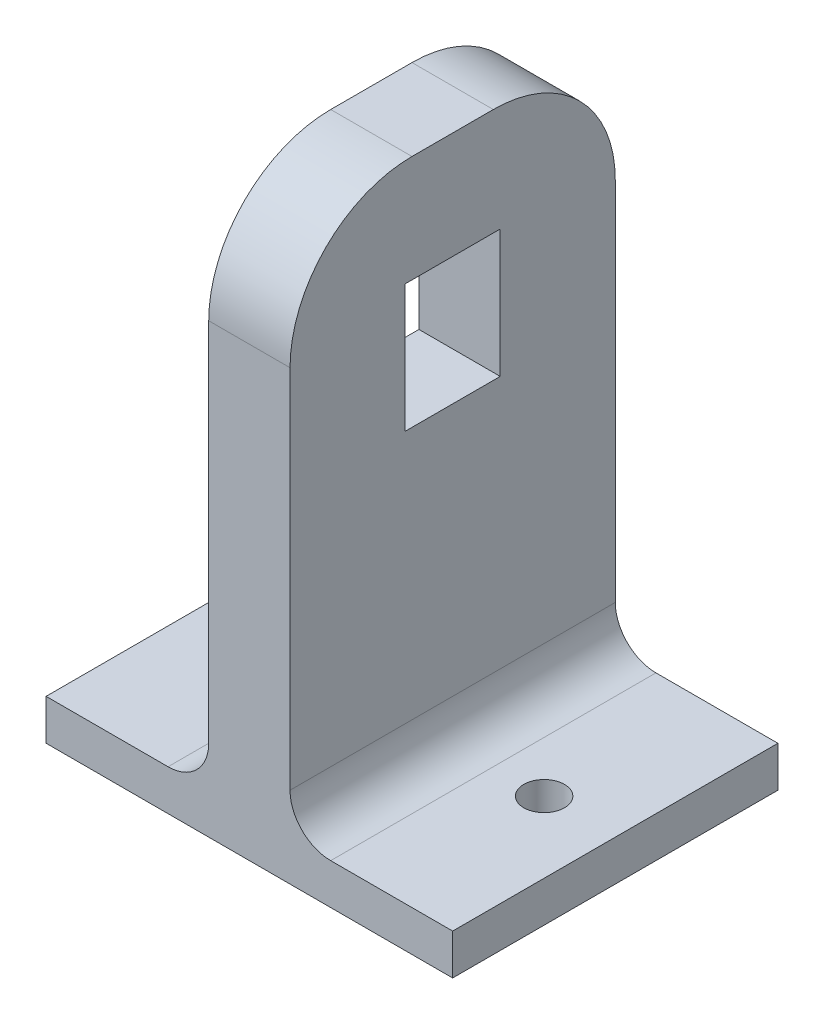
SolidWorks part; units mm, degrees
material "ABS"
ref_plane "Front Plane" through (0, 0, 0) normal (0, 0, 1) x (1, 0, 0)
ref_plane "Top Plane" through (0, 0, 0) normal (0, 1, 0) x (1, 0, 0)
ref_plane "Right Plane" through (0, 0, 0) normal (1, 0, 0) x (0, 0, -1)
sketch "Sketch1" plane through (0, 0, 0) normal (1, 0, 0) x (0, 0, -1)
  line L0 (0, -44.45) -> (0, 17.78) construction
  line L1 (-25.4, -44.45) -> (25.4, -44.45)
  line L2 (-25.4, -44.45) -> (-25.4, 44.45)
  line L3 (-25.4, 44.45) -> (25.4, 44.45)
  line L4 (25.4, -44.45) -> (25.4, 44.45)
  line L5 (-25.4, -44.45) -> (25.4, 44.45) construction
  line L6 (-25.4, 44.45) -> (25.4, -44.45) construction
  line L16 (-7.4295, 7.8105) -> (7.4295, 7.8105)
  line L17 (-7.4295, 7.8105) -> (-7.4295, 27.7495)
  line L18 (-7.4295, 27.7495) -> (7.4295, 27.7495)
  line L19 (7.4295, 7.8105) -> (7.4295, 27.7495)
  line L20 (-7.4295, 7.8105) -> (7.4295, 27.7495) construction
  line L21 (-7.4295, 27.7495) -> (7.4295, 7.8105) construction
  point P0 (0, 0)
  dimension "D1" = 88.9
  dimension "D2" = 50.8
  dimension "D3" = 62.23
  dimension "D4" = 19.939
  dimension "D5" = 14.859
extrude "Boss-Extrude1" add sketch "Sketch1" along normal mid plane 12.7
sketch "Sketch2" plane through (0, 0, 0) normal (1, 0, 0) x (0, 0, -1)
  line L0 (25.4, -44.45) -> (25.4, 44.45) construction
  line L1 (-25.4, -44.45) -> (25.4, -44.45)
  line L2 (-25.4, -44.45) -> (-25.4, -38.1)
  line L3 (-25.4, -38.1) -> (25.4, -38.1)
  line L4 (25.4, -44.45) -> (25.4, -38.1)
  dimension "D1" = 6.35
extrude "Boss-Extrude2" add sketch "Sketch2" along normal mid plane 63.5
fillet "Fillet1" radius 6.35 2 edges at (-6.35, -38.1, 0) (6.35, -38.1, 0)
sketch "Sketch3" plane through (0, -38.1, 0) normal (0, 1, 0) x (1, 0, 0)
  line L1 (31.75, 25.4) -> (31.75, -25.4) construction
  line L3 (-53.5691, 0) -> (53.5691, 0) construction
  circle A0 centre (20.6375, 0) radius 3.175
  point P2 (0, 0)
  dimension "D1" = 6.35
  dimension "D3" = 11.1125
extrude "Cut-Extrude1" cut sketch "Sketch3" against normal through all
mirror "Mirror1" about plane through (0, 0, 0) normal (1, 0, 0) of "Cut-Extrude1"
fillet "Fillet2" radius 19.05 2 edges at (0, 44.45, -25.4) (0, 44.45, 25.4)
